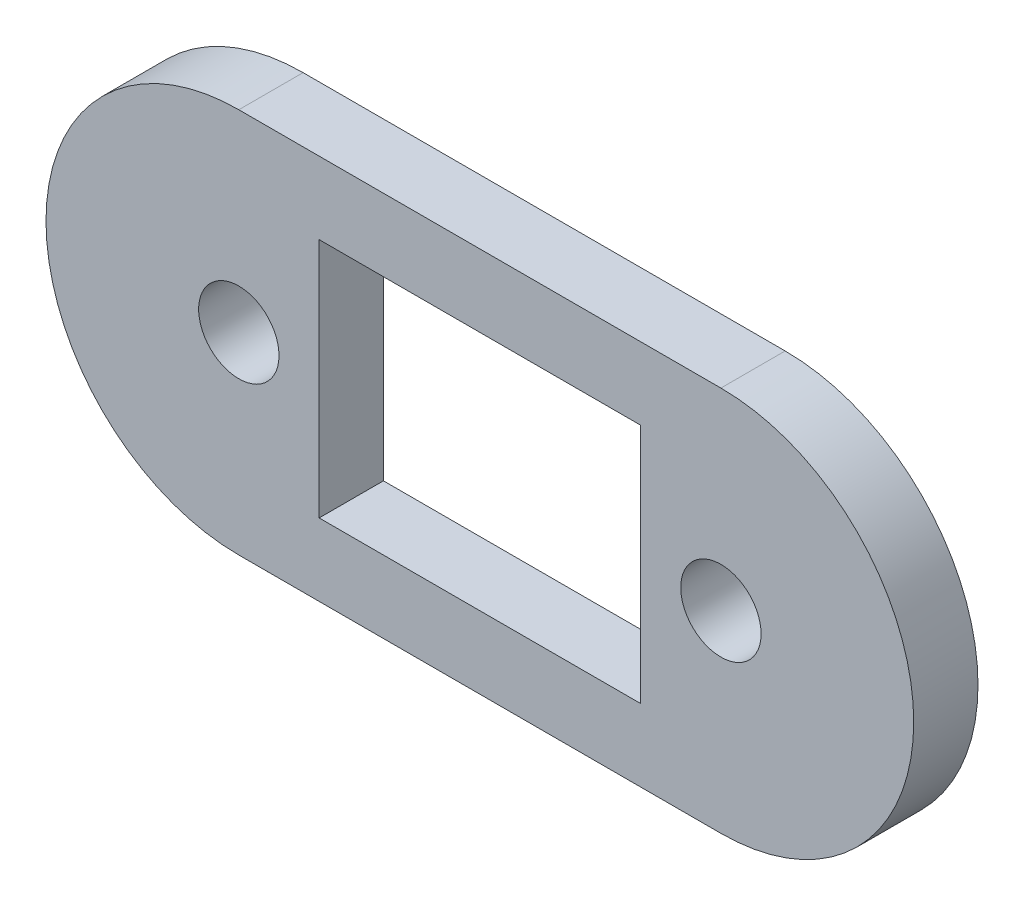
SolidWorks part; units mm, degrees
material "ABS PC"
ref_plane "Front Plane" through (0, 0, 0) normal (0, 0, 1) x (1, 0, 0)
ref_plane "Top Plane" through (0, 0, 0) normal (0, 1, 0) x (1, 0, 0)
ref_plane "Right Plane" through (0, 0, 0) normal (1, 0, 0) x (0, 0, -1)
sketch "Sketch1" plane through (0, 0, 0) normal (0, 0, 1) x (1, 0, 0)
  line L0 (-75, 0) -> (75, 0) construction
  line L1 (-75, 60) -> (75, 60)
  line L2 (-75, -60) -> (75, -60)
  line L4 (50, -37.5) -> (-50, -37.5)
  line L5 (50, -37.5) -> (50, 37.5)
  line L6 (50, 37.5) -> (-50, 37.5)
  line L7 (-50, -37.5) -> (-50, 37.5)
  line L8 (50, -37.5) -> (-50, 37.5) construction
  line L9 (50, 37.5) -> (-50, -37.5) construction
  arc A0 (-75, 60) -> (-75, -60) centre (-75, 0) ccw
  arc A1 (75, -60) -> (75, 60) centre (75, 0) ccw
  circle A2 centre (75, 0) radius 12.5
  circle A3 centre (-75, 0) radius 12.5
  point P2 (0, 0)
  point P8 (0, 0)
  dimension "D4" = 25
  dimension "D1" = 120
  dimension "D2" = 75
  dimension "D3" = 100
  dimension "D5" = 150
extrude "Boss-Extrude1" add sketch "Sketch1" along normal blind 20
